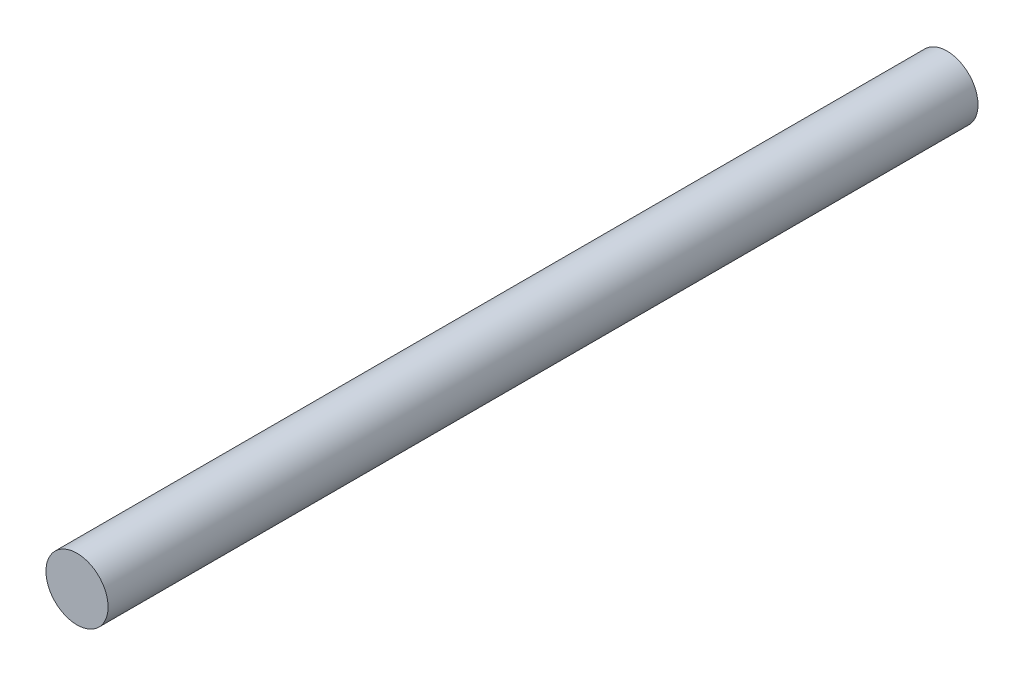
SolidWorks part; units mm, degrees
material "7075-O (SS)"
ref_plane "Front" through (0, 0, 0) normal (0, 0, 1) x (1, 0, 0)
ref_plane "Top" through (0, 0, 0) normal (0, 1, 0) x (1, 0, 0)
ref_plane "Right" through (0, 0, 0) normal (1, 0, 0) x (0, 0, -1)
sketch "Croquis1" plane through (0, 0, 0) normal (0, 0, 1) x (1, 0, 0)
  circle A0 centre (0, 0) radius 5
  dimension "D1" = 10
extrude "Saliente-Extruir1" add sketch "Croquis1" along normal mid plane 140
